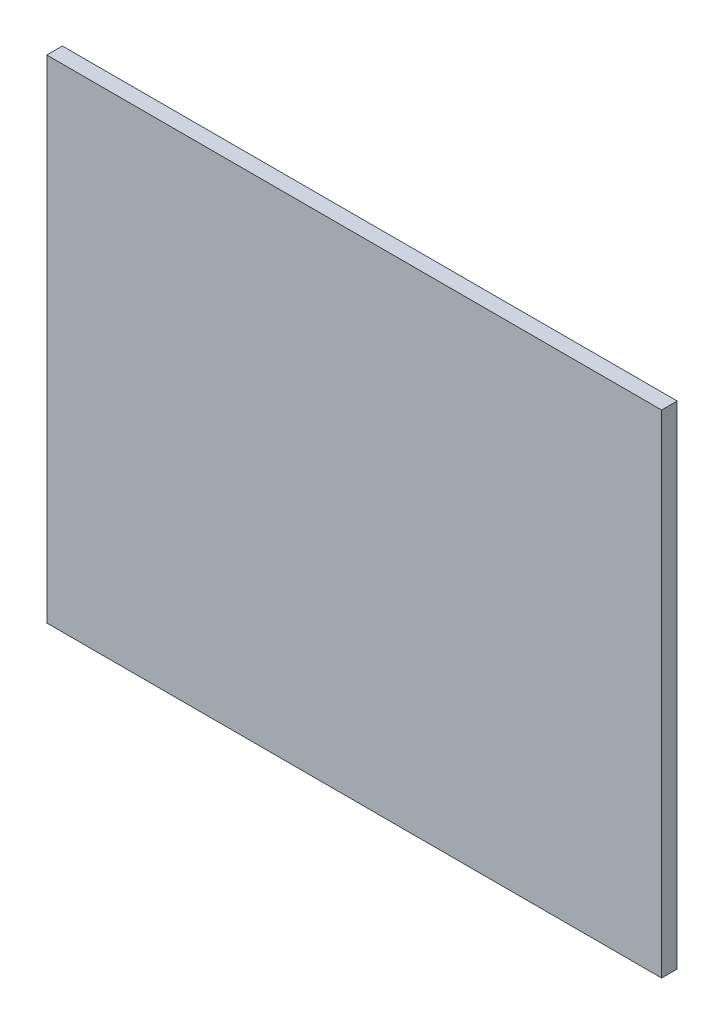
SolidWorks part; units mm, degrees
ref_plane "Front Plane" through (0, 0, 0) normal (0, 0, 1) x (1, 0, 0)
ref_plane "Top Plane" through (0, 0, 0) normal (0, 1, 0) x (1, 0, 0)
ref_plane "Right Plane" through (0, 0, 0) normal (1, 0, 0) x (0, 0, -1)
sketch "Sketch1" plane through (0, 0, 0) normal (0, 0, 1) x (1, 0, 0)
  line L1 (-301.7944, 154.841) -> (198.2056, 154.841)
  line L2 (-301.7944, 154.841) -> (-301.7944, -245.159)
  line L3 (-301.7944, -245.159) -> (198.2056, -245.159)
  line L4 (198.2056, 154.841) -> (198.2056, -245.159)
  dimension "D1" = 500
  dimension "D2" = 400
extrude "Boss-Extrude1" add sketch "Sketch1" along normal blind 12.7
